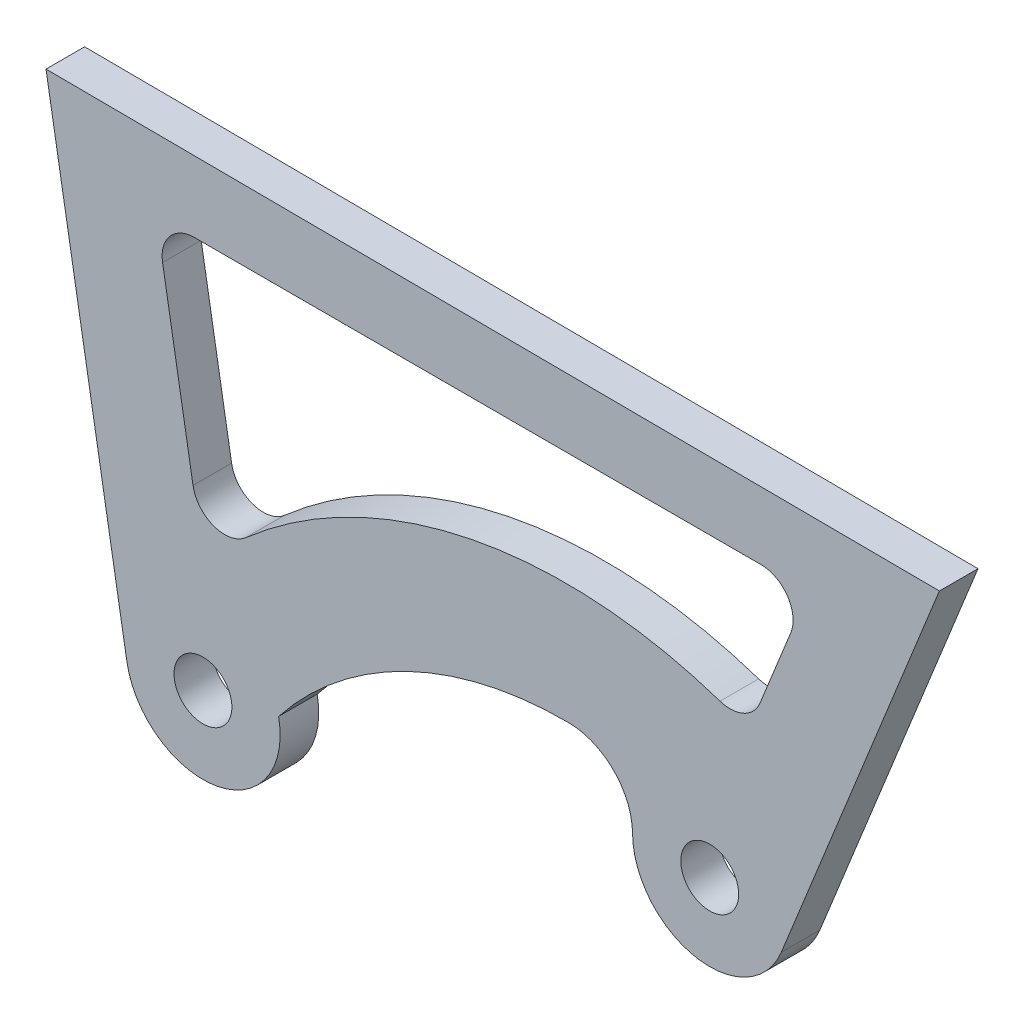
SolidWorks part; units mm, degrees
ref_plane "Front Plane" through (0, 0, 0) normal (0, 0, 1) x (1, 0, 0)
ref_plane "Top Plane" through (0, 0, 0) normal (0, 1, 0) x (1, 0, 0)
ref_plane "Right Plane" through (0, 0, 0) normal (1, 0, 0) x (0, 0, -1)
sketch "Sketch1" plane through (0, 0, 0) normal (0, 0, 1) x (1, 0, 0)
  line L0 (188.3479, -360.5695) -> (767.6545, -363.9867) construction
  line L1 (188.3479, -360.5695) -> (767.6545, -363.9867)
  line L2 (538.0871, -362.6325) -> (513.5103, -423.56)
  line L3 (399.1958, -361.8132) -> (411.7704, -435.2969)
  line L4 (514.9795, -379.8203) -> (510.21, -391.6443)
  line L5 (417.3194, -378.7932) -> (422.0504, -406.4398)
  line L6 (510.3426, -372.9498) -> (422.2478, -372.9498)
  circle A0 centre (423.5985, -433.2729) radius 4.5 construction
  circle A1 centre (502.3816, -419.0709) radius 4.5 construction
  circle A2 centre (423.5985, -433.2729) radius 4.5
  circle A3 centre (502.3816, -419.0709) radius 4.5
  arc A4 (490.3818, -419.1338) -> (513.5103, -423.56) centre (502.3816, -419.0709) ccw
  arc A5 (411.7704, -435.2969) -> (435.3584, -430.8845) centre (423.5985, -433.2729) ccw
  arc A6 (480.4562, -409.1865) -> (435.3584, -430.8845) centre (480.0337, -466.0238) ccw
  arc A7 (503.985, -394.515) -> (430.2776, -409.3537) centre (480.0337, -466.0238) ccw
  arc A8 (480.4562, -409.1865) -> (490.3818, -419.1338) centre (480.3819, -419.1863) cw
  arc A9 (510.21, -391.6443) -> (503.985, -394.515) centre (505.573, -389.7739) cw
  arc A10 (422.0504, -406.4398) -> (430.2776, -409.3537) centre (426.9787, -405.5964) ccw
  arc A11 (422.2478, -372.9498) -> (417.3194, -378.7932) centre (422.2478, -377.9498) ccw
  arc A12 (510.3426, -372.9498) -> (514.9795, -379.8203) centre (510.3426, -377.9498) cw
  dimension "D1" = 24
  dimension "D2" = 24
  dimension "D5" = 10
  dimension "D6" = 5
  dimension "D3" = 15
  dimension "D4" = 15
extrude "Boss-Extrude1" add sketch "Sketch1" against normal blind 6 contours A6 A8 A4 L2 L1 L3 A5 A2 A3 L6 A12 L4 A9 A7 A10 L5 A11
